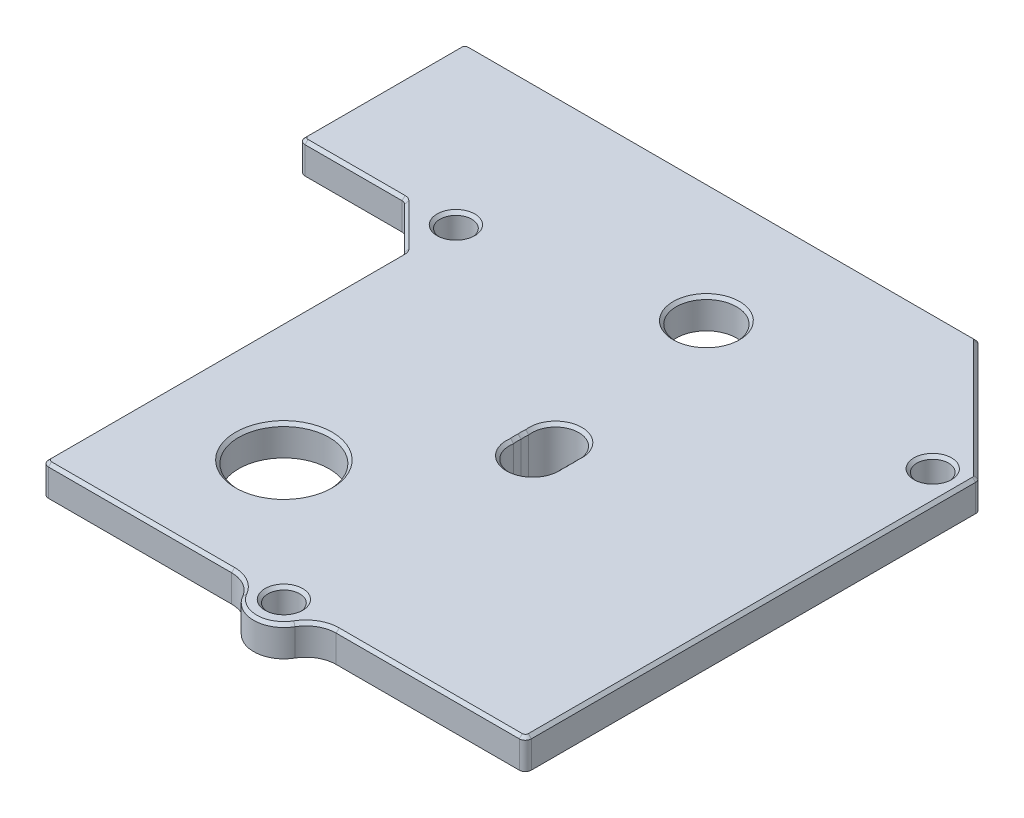
SolidWorks part; units mm, degrees
ref_plane "前视基准面" through (0, 0, 0) normal (0, 0, 1) x (1, 0, 0)
ref_plane "上视基准面" through (0, 0, 0) normal (0, 1, 0) x (1, 0, 0)
ref_plane "右视基准面" through (0, 0, 0) normal (1, 0, 0) x (0, 0, -1)
other "Configuration Table"
sketch "草图1" plane through (0, 0, 0) normal (0, 1, 0) x (1, 0, 0)
  line L0 (0.7016, -0.1135) -> (0.7016, 23.8865)
  line L5 (0.7016, 23.8865) -> (-2.2984, 26.8865)
  line L6 (-2.2984, 26.8865) -> (-9.2984, 26.8865)
  line L7 (-9.2984, 26.8865) -> (-9.2984, 37.8865)
  line L8 (-9.2984, 37.8865) -> (24.7016, 37.8865)
  line L9 (24.7016, 37.8865) -> (32.7016, 29.8865)
  line L10 (32.7016, 29.8865) -> (32.7016, -0.1135)
  line L11 (32.7016, -0.1135) -> (0.7016, -0.1135)
extrude "凸台-拉伸1" add sketch "草图1" along normal blind 2
sketch "草图2" plane through (0, 0, 0) normal (0, -1, 0) x (1, 0, 0)
  line L16 (32.7016, 0.1135) -> (0.7016, 0.1135)
  line L17 (0.7016, 0.1135) -> (0.7016, -23.8865)
  line L18 (0.7016, -23.8865) -> (-2.2984, -26.8865)
  line L19 (-2.2984, -26.8865) -> (-9.2984, -26.8865)
  line L20 (-9.2984, -26.8865) -> (-9.2984, -37.8865)
  line L21 (-9.2984, -37.8865) -> (24.7016, -37.8865)
  line L22 (24.7016, -37.8865) -> (32.7016, -29.8865)
  line L23 (32.7016, -29.8865) -> (32.7016, 0.1135)
  line L24 (32.7016, 0.1135) -> (0.7016, 0.1135)
  line L25 (0.7016, 0.1135) -> (0.7016, -23.8865)
  line L26 (0.7016, -23.8865) -> (-2.2984, -26.8865)
  line L27 (-2.2984, -26.8865) -> (-9.2984, -26.8865)
  line L28 (-9.2984, -26.8865) -> (-9.2984, -37.8865)
  line L29 (-9.2984, -37.8865) -> (24.7016, -37.8865)
  line L30 (24.7016, -37.8865) -> (32.7016, -29.8865)
  line L31 (32.7016, -29.8865) -> (32.7016, 0.1135)
  arc A2 (18.2313, -16.6365) -> (15.1719, -16.6365) centre (16.7016, -16.3865) ccw
  arc A3 (15.1719, -16.6365) -> (15.1719, -17.1365) centre (16.7016, -16.8865) ccw
  arc A4 (15.1719, -17.1365) -> (15.1719, -17.6365) centre (16.7016, -17.3865) ccw
  arc A5 (18.2313, -17.1365) -> (18.2313, -16.6365) centre (16.7016, -16.8865) ccw
  arc A6 (18.2313, -17.6365) -> (18.2313, -17.1365) centre (16.7016, -17.3865) ccw
  arc A8 (15.1719, -17.6365) -> (18.2313, -17.6365) centre (16.7016, -17.8865) ccw
  circle A9 centre (16.7016, -17.1365) radius 3.5
  dimension "D2" = 7
  dimension "D1" = 0
extrude "凸台-拉伸2" add sketch "草图2" along normal blind 5.7 contours A9 A8 A4 A3 A2 A5 A6
sketch "草图3" plane through (0, 0, 0) normal (0, -1, 0) x (1, 0, 0)
  arc A9 (18.2313, -17.6365) -> (18.2313, -17.1365) centre (16.7016, -17.3865) ccw
  arc A10 (18.2313, -17.1365) -> (18.2313, -16.6365) centre (16.7016, -16.8865) ccw
  arc A11 (18.2313, -16.6365) -> (15.1719, -16.6365) centre (16.7016, -16.3865) ccw
  arc A12 (18.2313, -17.6365) -> (18.2313, -17.1365) centre (16.7016, -17.3865) ccw
  arc A13 (18.2313, -17.1365) -> (18.2313, -16.6365) centre (16.7016, -16.8865) ccw
  arc A14 (18.2313, -16.6365) -> (15.1719, -16.6365) centre (16.7016, -16.3865) ccw
  arc A24 (15.1719, -17.6365) -> (18.2313, -17.6365) centre (16.7016, -17.8865) ccw
  arc A25 (18.2313, -17.6365) -> (18.2313, -17.1365) centre (16.7016, -17.3865) ccw
  arc A26 (18.2313, -17.1365) -> (18.2313, -16.6365) centre (16.7016, -16.8865) ccw
  arc A27 (18.2313, -16.6365) -> (15.1719, -16.6365) centre (16.7016, -16.3865) ccw
  arc A28 (15.1719, -16.6365) -> (15.1719, -17.1365) centre (16.7016, -16.8865) ccw
  arc A29 (15.1719, -17.1365) -> (15.1719, -17.6365) centre (16.7016, -17.3865) ccw
  arc A30 (15.1719, -17.6365) -> (18.2313, -17.6365) centre (16.7016, -17.8865) ccw
  arc A31 (18.2313, -17.6365) -> (18.2313, -17.1365) centre (16.7016, -17.3865) ccw
  arc A32 (18.2313, -17.1365) -> (18.2313, -16.6365) centre (16.7016, -16.8865) ccw
  arc A33 (18.2313, -16.6365) -> (15.1719, -16.6365) centre (16.7016, -16.3865) ccw
  arc A34 (15.1719, -16.6365) -> (15.1719, -17.1365) centre (16.7016, -16.8865) ccw
  arc A35 (15.1719, -17.1365) -> (15.1719, -17.6365) centre (16.7016, -17.3865) ccw
  arc M10 (15.1719, -17.6365) -> (18.2313, -17.6365) centre (16.7016, -17.8865) ccw
  arc M11 (18.2313, -17.6365) -> (18.2313, -17.1365) centre (16.7016, -17.3865) ccw
  arc M12 (18.2313, -17.1365) -> (18.2313, -16.6365) centre (16.7016, -16.8865) ccw
  arc M13 (18.2313, -16.6365) -> (15.1719, -16.6365) centre (16.7016, -16.3865) ccw
  arc M14 (15.1719, -16.6365) -> (15.1719, -17.1365) centre (16.7016, -16.8865) ccw
  arc M15 (15.1719, -17.1365) -> (15.1719, -17.6365) centre (16.7016, -17.3865) ccw
  dimension "D1" = 0
  dimension "D2" = 0
extrude "切除-拉伸1" cut sketch "草图3" against normal blind 4.7 contours M15 M10 M11 M12 M13 M14
sketch "草图5" plane through (0, 0, 0) normal (0, -1, 0) x (1, 0, 0)
  circle A0 centre (30.7016, -28.8865) radius 1.05
  circle A1 centre (0.9016, -27.0865) radius 1.05
  dimension "D1" = 2.1
  dimension "D2" = 2.1
extrude "切除-拉伸2" cut sketch "草图5" against normal blind 10
sketch "草图6" plane through (0, 0, 0) normal (0, -1, 0) x (-1, 0, 0)
  line L0 (-0.7016, -0.1135) -> (-32.7016, -0.1135) construction
  circle A0 centre (-16.7016, -0.1135) radius 2
  dimension "D1" = 4
extrude "凸台-拉伸3" add sketch "草图6" against normal blind 2
fillet "圆角1" radius 2 2 edges at (18.7016, 1, 0.1135) (14.7016, 1, 0.1135)
sketch "草图7" plane through (0, 2, 0) normal (0, 1, 0) x (1, 0, 0)
  circle A0 centre (16.7016, -0.1135) radius 1.05
  dimension "D1" = 2.1
extrude "切除-拉伸3" cut sketch "草图7" against normal blind 2
fillet "圆角2" radius 0.4 8 edges at (24.7016, 1, -37.8865) (32.7016, 1, -29.8865) (32.7016, 1, 0.1135) (0.7016, 1, 0.1135) (0.7016, 1, -23.8865) (-2.2984, 1, -26.8865) (-9.2984, 1, -37.8865) (-9.2984, 1, -26.8865)
chamfer "倒角1" distance 2 angle 45 1 edges at (16.7016, 0, -20.6365)
chamfer "倒角2" distance 0.4 angle 45 1 edges at (16.7016, -5.7, -20.6365)
sketch "草图8" plane through (0, 0, 0) normal (0, -1, 0) x (1, 0, 0)
  line L0 (0.7016, -23.7208) -> (0.7016, -0.2865) construction
  line L1 (1.1016, 0.1135) -> (13.2375, 0.1135) construction
  line L2 (24.5359, -37.8865) -> (-8.8984, -37.8865) construction
  line L3 (-9.2984, -37.4865) -> (-9.2984, -27.2865) construction
  circle A0 centre (8.7016, -7.8865) radius 3
  circle A1 centre (14.7016, -29.8865) radius 2
  dimension "D1" = 6
  dimension "D4" = 4
  dimension "D6" = 24
  dimension "D2" = 8
  dimension "D3" = 8
  dimension "D5" = 8
extrude "切除-拉伸5" cut sketch "草图8" against normal through all
chamfer "倒角3" distance 0.2 angle 45 31 edges at (32.6712, 2, -29.8739) (32.7016, 2, -15.0037) (32.5845, 2, -0.0037) (26.2337, 2, 0.1135) (19.1657, 2, 0.3815) (16.7016, 2, 2.1135) (14.2375, 2, 0.3815) (7.1696, 2, 0.1135) (0.8188, 2, -0.0037) (0.7016, 2, -12.0037) (0.6712, 2, -23.8739) (-0.7984, 2, -25.3865) (-2.311, 2, -26.8561) (-5.6812, 2, -26.8865) (-9.1812, 2, -27.0037) (-9.2984, 2, -32.3865) (-9.1812, 2, -37.7693) (7.8188, 2, -37.8865) (24.689, 2, -37.8561) (28.7016, 2, -33.8865) (16.7016, 2, -14.8365) (15.1516, 2, -16.8865) (18.2516, 2, -16.8865) (15.1516, 2, -17.3865) (18.2516, 2, -17.3865) (16.7016, 2, -19.4365) (0.9016, 2, -28.1365) (30.7016, 2, -29.9365) (16.7016, 2, 1.1635) (14.7016, 2, -31.8865) (8.7016, 2, -10.8865)
